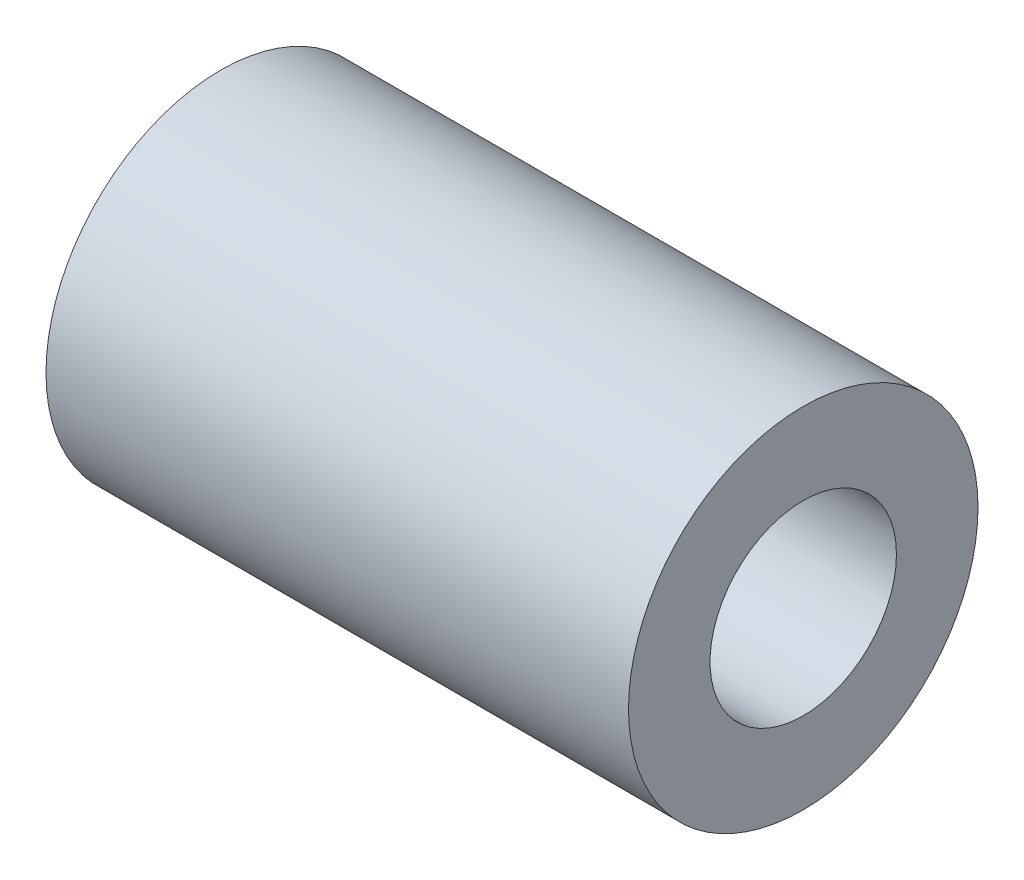
SolidWorks part; units mm, degrees
ref_plane "前视基准面" through (0, 0, 0) normal (0, 0, 1) x (1, 0, 0)
ref_plane "上视基准面" through (0, 0, 0) normal (0, 1, 0) x (1, 0, 0)
ref_plane "右视基准面" through (0, 0, 0) normal (1, 0, 0) x (0, 0, -1)
sketch "草图1" plane through (0, 0, 0) normal (1, 0, 0) x (0, 0, -1)
  circle A0 centre (0, 0) radius 7.5
extrude "凸台-拉伸1" add sketch "草图1" along normal blind 25
sketch "草图2" plane through (0, 0, 0) normal (-1, 0, 0) x (0, 0, 1)
  circle A0 centre (0, 0) radius 2.5
extrude "切除-拉伸1" cut sketch "草图2" against normal blind 12.5
sketch "草图3" plane through (25, 0, 0) normal (1, 0, 0) x (0, 0, -1)
  circle A0 centre (0, 0) radius 4
extrude "切除-拉伸2" cut sketch "草图3" against normal blind 12.5
